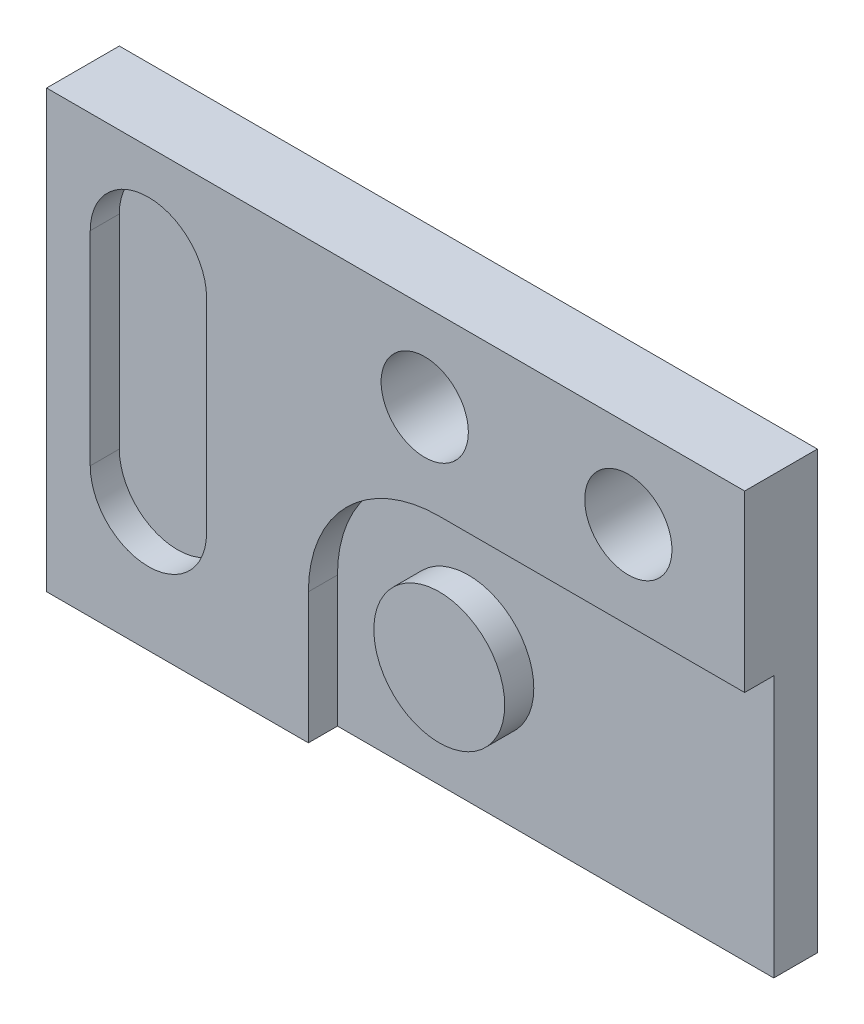
SolidWorks part; units mm, degrees
ref_plane "Front Plane" through (0, 0, 0) normal (0, 0, 1) x (1, 0, 0)
ref_plane "Top Plane" through (0, 0, 0) normal (0, 1, 0) x (1, 0, 0)
ref_plane "Right Plane" through (0, 0, 0) normal (1, 0, 0) x (0, 0, -1)
sketch "Sketch1" plane through (0, 0, 0) normal (0, 0, 1) x (1, 0, 0)
  line L1 (-120, -75) -> (120, -75)
  line L2 (-120, -75) -> (-120, 75)
  line L3 (-120, 75) -> (120, 75)
  line L4 (120, -75) -> (120, 75)
  line L5 (-120, -75) -> (120, 75) construction
  line L6 (-120, 75) -> (120, -75) construction
  point P0 (0, 0)
  dimension "D1" = 150
  dimension "D2" = 240
extrude "Boss-Extrude1" add sketch "Sketch1" along normal blind 25
sketch "Sketch2" plane through (0, 0, 25) normal (0, 0, 1) x (1, 0, 0)
  line L0 (-85, -30) -> (-85, 40) construction
  line L1 (-105, -30) -> (-105, 40)
  line L2 (-65, -30) -> (-65, 40)
  line L8 (15, 15) -> (120, 15)
  line L9 (120, -75) -> (120, 75) construction
  line L10 (-30, -30) -> (-30, -75)
  line L11 (-120, 75) -> (-120, -75) construction
  line L12 (120, 15) -> (120, -75)
  line L13 (-30, -75) -> (120, -75)
  line L14 (120, 75) -> (-120, 75) construction
  arc A0 (-105, -30) -> (-65, -30) centre (-85, -30) ccw
  arc A1 (-65, 40) -> (-105, 40) centre (-85, 40) ccw
  circle A2 centre (10, 45) radius 15
  circle A3 centre (80, 45) radius 15
  circle A4 centre (15, -30) radius 22.5
  arc A5 (15, 15) -> (-30, -30) centre (15, -30) ccw
  point P1 (-85, 5)
  dimension "D2" = 45
  dimension "D4" = 45
  dimension "D5" = 30
  dimension "D9" = 30
  dimension "D15" = 20
  dimension "D1" = 90
  dimension "D3" = 105
  dimension "D6" = 40
  dimension "D7" = 30
  dimension "D8" = 70
  dimension "D10" = 30
  dimension "D11" = 0
  dimension "D12" = 35
  dimension "D13" = 35
  dimension "D14" = 70
extrude "Cut-Extrude1" cut sketch "Sketch2" against normal blind 10
sketch "Sketch3" plane through (0, 0, 15) normal (0, 0, 1) x (1, 0, 0)
  circle A0 centre (80, 45) radius 15 construction
  circle A1 centre (10, 45) radius 15
  circle A2 centre (10, 45) radius 15
  circle A3 centre (80, 45) radius 15
  dimension "D1" = 0
extrude "Cut-Extrude2" cut sketch "Sketch3" against normal through all
